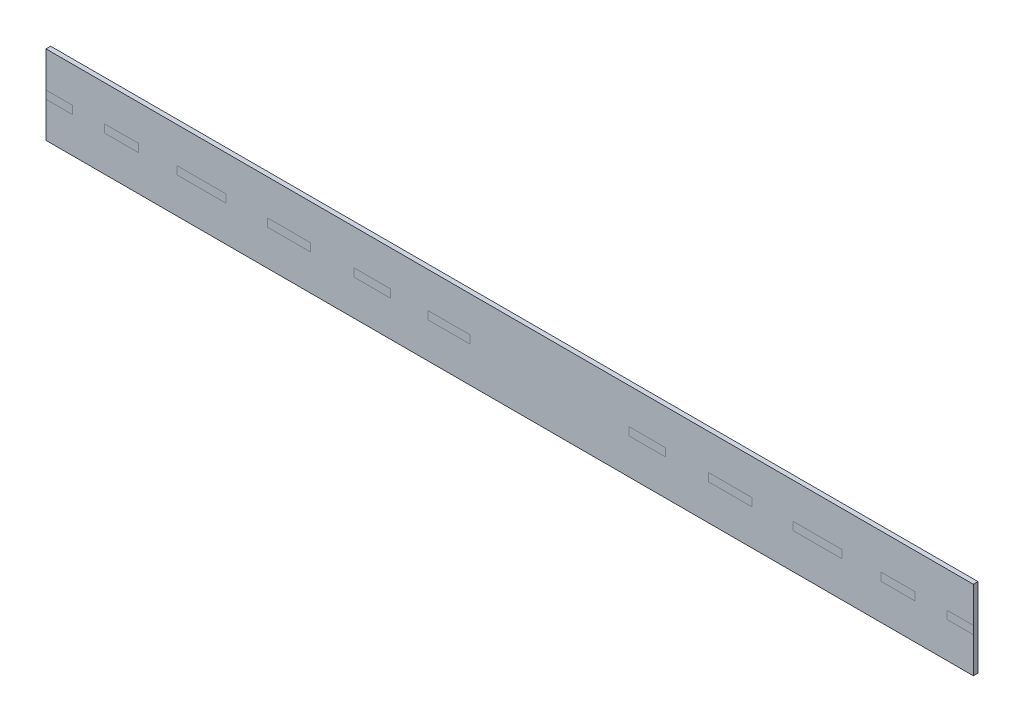
SolidWorks part; units mm, degrees
ref_plane "Front Plane" through (0, 0, 0) normal (0, 0, 1) x (1, 0, 0)
ref_plane "Top Plane" through (0, 0, 0) normal (0, 1, 0) x (1, 0, 0)
ref_plane "Right Plane" through (0, 0, 0) normal (1, 0, 0) x (0, 0, -1)
sketch "Sketch1" plane through (0, 0, 0) normal (0, 0, 1) x (1, 0, 0)
  line L1 (-1000, 85.5) -> (1000, 85.5)
  line L2 (-1000, 85.5) -> (-1000, -85.5)
  line L3 (-1000, -85.5) -> (1000, -85.5)
  line L4 (1000, 85.5) -> (1000, -85.5)
  line L5 (-1000, 85.5) -> (1000, -85.5) construction
  line L6 (-1000, -85.5) -> (1000, 85.5) construction
  point P0 (0, 0)
  dimension "D1" = 171
  dimension "D2" = 2000
extrude "Boss-Extrude1" add sketch "Sketch1" along normal blind 10
ref_plane "Plane1" through (0, 0, 120) normal (0, 0, 1) x (1, 0, 0)
sketch "Sketch2" plane through (0, 0, 120) normal (0, 0, 1) x (1, 0, 0)
  line L0 (-1000, 0) -> (-943.3395, 0) construction
  line L1 (-1000, 85.5) -> (-1000, -85.5) construction
  line L2 (1000, -85.5) -> (1000, 85.5) construction
  line L3 (-943.3395, 8.6815) -> (-943.3395, -8.6815)
  line L4 (-1000, 8.6815) -> (-943.3395, 8.6815)
  line L5 (-1000, 8.6815) -> (-1000, -8.6815)
  line L6 (-1000, -8.6815) -> (-943.3395, -8.6815)
  line L7 (1000, 8.6815) -> (1000, -8.6815)
  line L8 (-1000, 8.6815) -> (-943.3395, 8.1896) construction
  line L9 (-1000, -8.6815) -> (-943.3395, -8.1896) construction
  line L10 (-874.0781, 8.6815) -> (-874.0781, -8.6815)
  line L11 (-800.7426, 8.6815) -> (-800.7426, -8.6815)
  line L12 (-717.2215, 8.6815) -> (-717.2215, -8.6815)
  line L13 (-611.2924, 8.6815) -> (-611.2924, -8.6815)
  line L14 (-522.6786, 8.6815) -> (-522.6786, -8.6815)
  line L15 (-429.0807, 8.6815) -> (-429.0807, -8.6815)
  line L16 (-336.2475, 8.6815) -> (-336.2475, -8.6815)
  line L17 (-257.0983, 8.6815) -> (-257.0983, -8.6815)
  line L18 (-175.918, 8.6815) -> (-175.918, -8.6815)
  line L19 (-85.4702, 8.6815) -> (-85.4702, -8.6815)
  line L20 (0, 8.6815) -> (0, -8.6815) construction
  line L21 (943.3395, 8.6815) -> (943.3395, -8.6815)
  line L22 (874.0781, 8.6815) -> (874.0781, -8.6815)
  line L23 (800.7426, 8.6815) -> (800.7426, -8.6815)
  line L24 (717.2215, 8.6815) -> (717.2215, -8.6815)
  line L25 (611.2924, 8.6815) -> (611.2924, -8.6815)
  line L26 (522.6786, 8.6815) -> (522.6786, -8.6815)
  line L27 (429.0807, 8.6815) -> (429.0807, -8.6815)
  line L28 (336.2475, 8.6815) -> (336.2475, -8.6815)
  line L29 (257.0983, 8.6815) -> (257.0983, -8.6815)
  line L30 (175.918, 8.6815) -> (175.918, -8.6815)
  line L31 (85.4702, 8.6815) -> (85.4702, -8.6815)
  line L32 (-874.0781, 8.6815) -> (-800.7426, 8.6815)
  line L33 (-874.0781, 7.5883) -> (-800.7426, 6.9517) construction
  line L34 (-874.0781, 0) -> (-800.7426, 0) construction
  line L35 (-874.0781, -7.5883) -> (-800.7426, -6.9517) construction
  line L36 (-874.0781, -8.6815) -> (-800.7426, -8.6815)
  line L37 (-717.2215, 8.6815) -> (-611.2924, 8.6815)
  line L38 (-717.2215, 6.2266) -> (-611.2924, 5.307) construction
  line L39 (-717.2215, 0) -> (-611.2924, 0) construction
  line L40 (-717.2215, -6.2266) -> (-611.2924, -5.307) construction
  line L41 (-717.2215, -8.6815) -> (-611.2924, -8.6815)
  line L42 (-522.6786, 8.6815) -> (-429.0807, 8.6815)
  line L43 (-522.6786, 4.5377) -> (-429.0807, 3.7251) construction
  line L44 (-522.6786, 0) -> (-429.0807, 0) construction
  line L45 (-522.6786, -4.5377) -> (-429.0807, -3.7251) construction
  line L46 (-522.6786, -8.6815) -> (-429.0807, -8.6815)
  line L47 (-336.2475, 8.6815) -> (-257.0983, 8.6815)
  line L48 (-336.2475, 2.9191) -> (-257.0983, 2.232) construction
  line L49 (-336.2475, 0) -> (-257.0983, 0) construction
  line L50 (-336.2475, -2.9191) -> (-257.0983, -2.232) construction
  line L51 (-336.2475, -8.6815) -> (-257.0983, -8.6815)
  line L52 (-175.918, 8.6815) -> (-85.4702, 8.6815)
  line L53 (-175.918, 1.5272) -> (-85.4702, 0.742) construction
  line L54 (-175.918, 0) -> (-85.4702, 0) construction
  line L55 (-175.918, -1.5272) -> (-85.4702, -0.742) construction
  line L56 (-175.918, -8.6815) -> (-85.4702, -8.6815)
  line L57 (0, 8.6815) -> (175.918, 8.6815)
  line L58 (0, 0) -> (175.918, -1.5272) construction
  line L59 (0, 0) -> (175.918, 0) construction
  line L60 (0, 0) -> (175.918, 1.5272) construction
  line L61 (0, -8.6815) -> (175.918, -8.6815)
  line L62 (257.0983, 8.6815) -> (336.2475, 8.6815)
  line L63 (257.0983, 2.232) -> (336.2475, 2.9191) construction
  line L64 (257.0983, 0) -> (336.2475, 0) construction
  line L65 (257.0983, -2.232) -> (336.2475, -2.9191) construction
  line L66 (257.0983, -8.6815) -> (336.2475, -8.6815)
  line L67 (429.0807, 8.6815) -> (522.6786, 8.6815)
  line L68 (429.0807, 3.7251) -> (522.6786, 4.5377) construction
  line L69 (429.0807, 0) -> (522.6786, 0) construction
  line L70 (429.0807, -3.7251) -> (522.6786, -4.5377) construction
  line L71 (429.0807, -8.6815) -> (522.6786, -8.6815)
  line L72 (611.2924, 8.6815) -> (717.2215, 8.6815)
  line L73 (611.2924, 5.307) -> (717.2215, 6.2266) construction
  line L74 (611.2924, 0) -> (717.2215, 0) construction
  line L75 (611.2924, -5.307) -> (717.2215, -6.2266) construction
  line L76 (611.2924, -8.6815) -> (717.2215, -8.6815)
  line L77 (800.7426, 8.6815) -> (874.0781, 8.6815)
  line L78 (800.7426, 6.9517) -> (874.0781, 7.5883) construction
  line L79 (800.7426, 0) -> (874.0781, 0) construction
  line L80 (800.7426, -6.9517) -> (874.0781, -7.5883) construction
  line L81 (800.7426, -8.6815) -> (874.0781, -8.6815)
  line L82 (943.3395, 8.6815) -> (1000, 8.6815)
  line L83 (943.3395, 8.1896) -> (1000, 8.6815) construction
  line L84 (943.3395, 0) -> (1000, 0) construction
  line L85 (943.3395, -8.1896) -> (1000, -8.6815) construction
  line L86 (943.3395, -8.6815) -> (1000, -8.6815)
  point P6 (0, 0)
split line "Split Line1"
